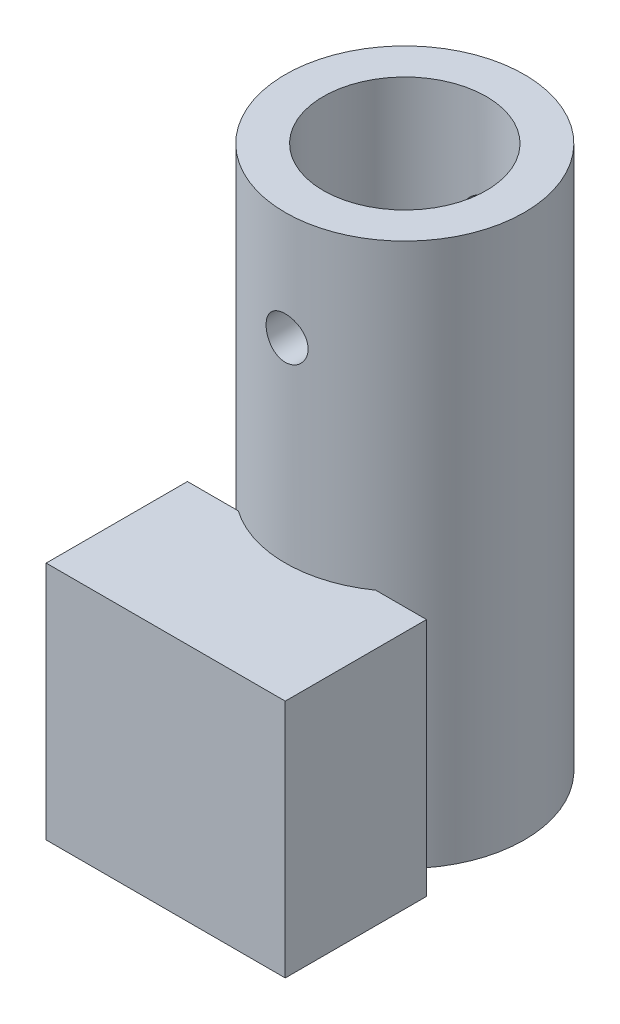
SolidWorks part; units mm, degrees
ref_plane "前基準面" through (0, 0, 0) normal (0, 0, 1) x (1, 0, 0)
ref_plane "上基準面" through (0, 0, 0) normal (0, 1, 0) x (1, 0, 0)
ref_plane "右基準面" through (0, 0, 0) normal (1, 0, 0) x (0, 0, -1)
sketch "草圖1" plane through (0, 0, 0) normal (0, 1, 0) x (1, 0, 0)
  circle A0 centre (0, 0) radius 11
  dimension "D1" = 22
extrude "填料-伸長1" add sketch "草圖1" along normal blind 50
sketch "草圖2" plane through (0, 50, 0) normal (0, 1, 0) x (1, 0, 0)
  circle A0 centre (0, 0) radius 7.5
  dimension "D1" = 15
extrude "除料-伸長1" cut sketch "草圖2" against normal through all
ref_plane "平面1" through (0, 0, 12) normal (0, 0, 1) x (1, 0, 0)
sketch "草圖4" plane through (0, 0, 12) normal (0, 0, 1) x (1, 0, 0)
  line L0 (0, 50) -> (0, 30) construction
  line L1 (7.5, 50) -> (-7.5, 50) construction
  circle A1 centre (0, 40) radius 1.935
  dimension "D3" = 3.87
  dimension "D1" = 20
extrude "除料-伸長4" cut sketch "草圖4" against normal blind 50
ref_plane "平面2" through (11, 0, 0) normal (1, 0, 0) x (0, 0, -1)
sketch "草圖6" plane through (0, 0, 12) normal (0, 0, 1) x (1, 0, 0)
  line L0 (0, 38.065) -> (0, 22.065) construction
  circle A0 centre (0, 40) radius 1.935 construction
  dimension "D1" = 16
sketch "草圖8" plane through (11, 0, 0) normal (1, 0, 0) x (0, 0, -1)
  line L0 (-12, 22.065) -> (12.0865, 22.065) construction
  line L1 (-12, 38.065) -> (-12, 22.065) construction
  line L2 (-12, 39.6358) -> (-12, -39.6358) construction
sketch "草圖11" plane through (0, 0, 12) normal (0, 0, 1) x (1, 0, 0)
  line L0 (-11, 22.065) -> (11, 22.065)
  line L1 (-11, 50) -> (-11, 0) construction
  line L2 (11, 22.065) -> (11, 0)
  line L3 (11, -33.6925) -> (11, 33.6925) construction
  line L4 (11, 0) -> (-11, 0)
  line L5 (-11, 0) -> (-11, 22.065)
extrude "填料-伸長3" add sketch "草圖11" along normal blind 10 and the other way blind 3
sketch "草圖12" plane through (0, 22.065, 0) normal (0, 1, 0) x (1, 0, 0)
  line L0 (0, -22) -> (0, -20.3047) construction
  line L1 (11, -22) -> (-11, -22) construction
